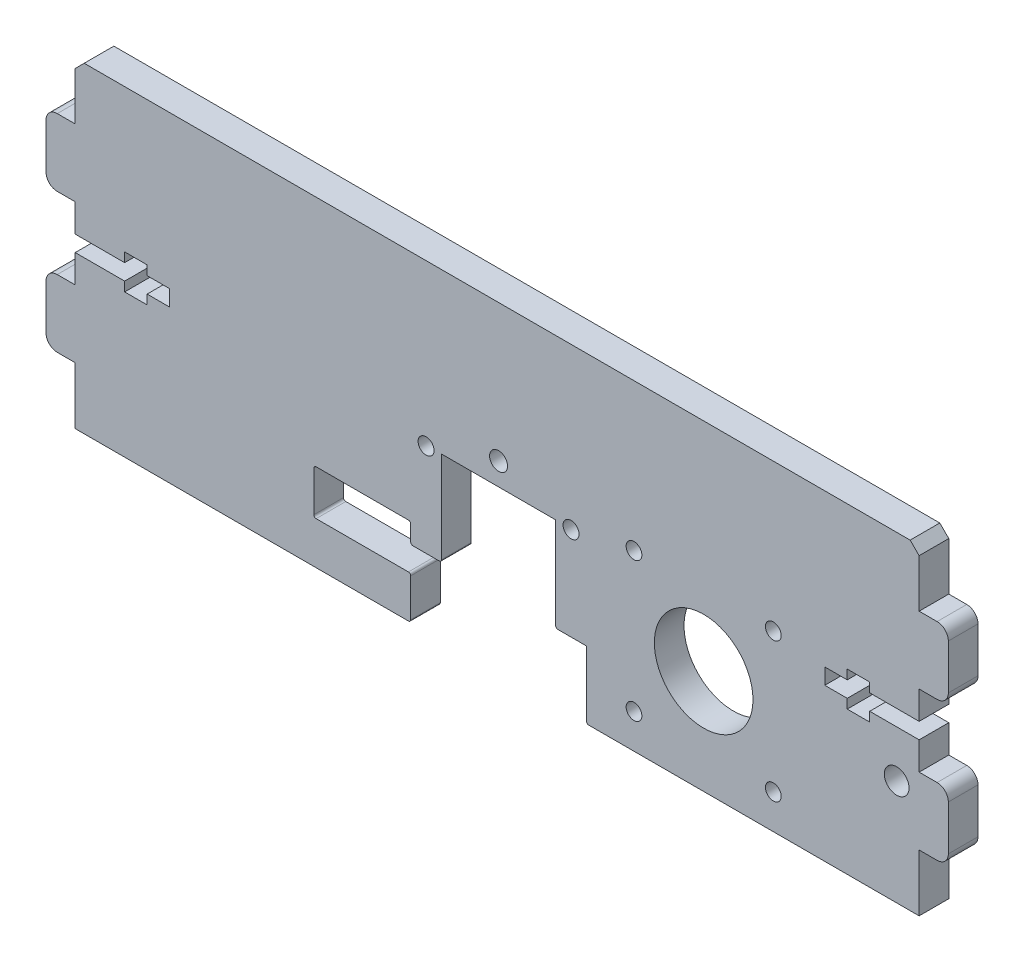
SolidWorks part; units mm, degrees
ref_plane "Front Plane" through (0, 0, 0) normal (0, 0, 1) x (1, 0, 0)
ref_plane "Top Plane" through (0, 0, 0) normal (0, 1, 0) x (1, 0, 0)
ref_plane "Right Plane" through (0, 0, 0) normal (1, 0, 0) x (0, 0, -1)
sketch "Model" plane through (0, 0, 0) normal (0, 0, 1) x (1, 0, 0)
  line L0 (0, 0) -> (74.15, 0)
  line L1 (0, 12.7) -> (0, 0)
  line L2 (-6.5, 25.2) -> (-6.5, 15.2)
  line L3 (0, 27.7) -> (-4, 27.7)
  line L4 (0, 33.935) -> (11, 33.935)
  line L5 (11, 33.935) -> (11, 31.85)
  line L6 (11, 31.85) -> (16, 31.85)
  line L7 (16, 31.85) -> (16, 33.935)
  line L8 (16, 33.935) -> (21, 33.935)
  line L9 (21, 33.935) -> (21, 37.485)
  line L10 (21, 37.485) -> (16, 37.485)
  line L11 (16, 37.485) -> (16, 39.57)
  line L12 (16, 39.57) -> (11, 39.57)
  line L13 (11, 39.57) -> (11, 37.485)
  line L14 (11, 37.485) -> (0, 37.485)
  line L15 (0, 43.72) -> (0, 37.485)
  line L16 (-4, 43.72) -> (0, 43.72)
  line L17 (-6.5, 56.22) -> (-6.5, 46.22)
  line L18 (0, 58.72) -> (-4, 58.72)
  line L19 (0, 69.42) -> (0, 58.72)
  line L20 (2, 71.42) -> (0, 69.42)
  line L21 (185.8, 71.42) -> (2, 71.42)
  line L22 (187.8, 69.42) -> (185.8, 71.42)
  line L23 (187.8, 58.72) -> (187.8, 69.42)
  line L24 (191.8, 58.72) -> (187.8, 58.72)
  line L25 (194.3, 46.22) -> (194.3, 56.22)
  line L26 (187.8, 43.72) -> (191.8, 43.72)
  line L27 (187.8, 37.485) -> (187.8, 43.72)
  line L28 (187.8, 37.485) -> (176.8, 37.485)
  line L29 (176.8, 37.485) -> (176.8, 39.57)
  line L30 (176.8, 39.57) -> (171.8, 39.57)
  line L31 (171.8, 39.57) -> (171.8, 37.485)
  line L32 (171.8, 37.485) -> (166.8, 37.485)
  line L33 (166.8, 37.485) -> (166.8, 33.935)
  line L34 (166.8, 33.935) -> (171.8, 33.935)
  line L35 (171.8, 33.935) -> (171.8, 31.85)
  line L36 (171.8, 31.85) -> (176.8, 31.85)
  line L37 (176.8, 31.85) -> (176.8, 33.935)
  line L38 (176.8, 33.935) -> (187.8, 33.935)
  line L39 (187.8, 27.7) -> (187.8, 33.935)
  line L40 (191.8, 27.7) -> (187.8, 27.7)
  line L41 (194.3, 15.2) -> (194.3, 25.2)
  line L42 (187.8, 12.7) -> (191.8, 12.7)
  line L43 (187.8, 0) -> (187.8, 12.7)
  line L44 (114.27, 0) -> (187.8, 0)
  line L45 (113.77, 15) -> (113.77, 0.5)
  line L46 (113.77, 15) -> (107.41, 15)
  line L47 (106.91, 15.5) -> (106.91, 35.8748)
  line L48 (106.91, 35.8748) -> (81.51, 35.8748)
  line L49 (81.51, 35.8748) -> (81.51, 15.5)
  line L50 (81.01, 15) -> (75.15, 15)
  line L51 (74.65, 15.5) -> (74.65, 18.9557)
  line L52 (74.15, 19.4557) -> (53.61, 19.4557)
  line L53 (53.11, 18.9557) -> (53.11, 9.9613)
  line L54 (53.61, 9.4613) -> (74.15, 9.4613)
  line L55 (74.65, 0.5) -> (74.65, 8.9613)
  line L56 (-4, 12.7) -> (0, 12.7)
  line L57 (0, 33.935) -> (0, 27.7)
  circle A0 centre (155.352, 38.6748) radius 1.7526
  circle A1 centre (155.352, 7.6748) radius 1.7526
  circle A2 centre (124.352, 38.6748) radius 1.7526
  circle A3 centre (124.352, 7.6748) radius 1.7526
  circle A4 centre (139.852, 23.1748) radius 10.975
  circle A5 centre (94.21, 40.8748) radius 2
  circle A6 centre (182.8, 23.5) radius 2.75
  circle A7 centre (110.34, 35.71) radius 1.775
  circle A8 centre (78.08, 35.71) radius 1.775
  arc A9 (74.15, 0) -> (74.65, 0.5) centre (74.15, 0.5) ccw
  arc A10 (-6.5, 15.2) -> (-4, 12.7) centre (-4, 15.2) ccw
  arc A11 (-4, 27.7) -> (-6.5, 25.2) centre (-4, 25.2) ccw
  arc A12 (-6.5, 46.22) -> (-4, 43.72) centre (-4, 46.22) ccw
  arc A13 (-4, 58.72) -> (-6.5, 56.22) centre (-4, 56.22) ccw
  arc A14 (194.3, 56.22) -> (191.8, 58.72) centre (191.8, 56.22) ccw
  arc A15 (191.8, 43.72) -> (194.3, 46.22) centre (191.8, 46.22) ccw
  arc A16 (194.3, 25.2) -> (191.8, 27.7) centre (191.8, 25.2) ccw
  arc A17 (191.8, 12.7) -> (194.3, 15.2) centre (191.8, 15.2) ccw
  arc A18 (113.77, 0.5) -> (114.27, 0) centre (114.27, 0.5) ccw
  arc A19 (106.91, 15.5) -> (107.41, 15) centre (107.41, 15.5) ccw
  arc A20 (81.01, 15) -> (81.51, 15.5) centre (81.01, 15.5) ccw
  arc A21 (74.65, 15.5) -> (75.15, 15) centre (75.15, 15.5) ccw
  arc A22 (74.65, 18.9557) -> (74.15, 19.4557) centre (74.15, 18.9557) ccw
  arc A23 (53.61, 19.4557) -> (53.11, 18.9557) centre (53.61, 18.9557) ccw
  arc A24 (53.11, 9.9613) -> (53.61, 9.4613) centre (53.61, 9.9613) ccw
  arc A25 (74.65, 8.9613) -> (74.15, 9.4613) centre (74.15, 8.9613) ccw
extrude "Boss-Extrude1" add sketch "Model" along normal blind 6.6
